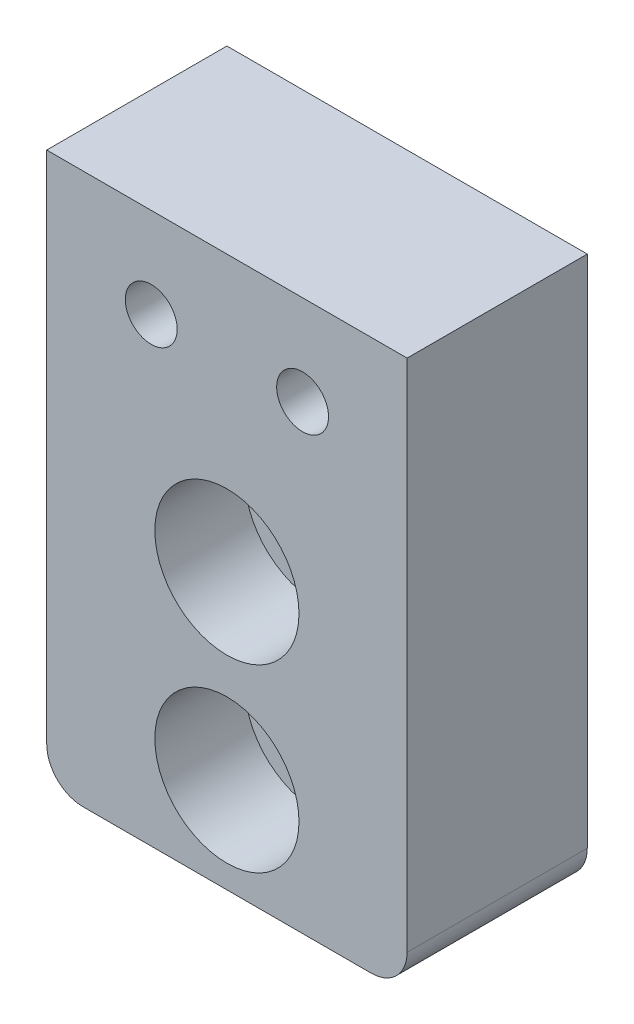
SolidWorks part; units mm, degrees
ref_plane "Front Plane" through (0, 0, 0) normal (0, 0, 1) x (1, 0, 0)
ref_plane "Top Plane" through (0, 0, 0) normal (0, 1, 0) x (1, 0, 0)
ref_plane "Right Plane" through (0, 0, 0) normal (1, 0, 0) x (0, 0, -1)
sketch "Sketch1" plane through (0, 0, 0) normal (0, 0, 1) x (1, 0, 0)
  line L1 (0, 0) -> (25.4, 0)
  line L2 (0, 0) -> (0, 38.8112)
  line L3 (0, 38.8112) -> (25.4, 38.8112)
  line L4 (25.4, 0) -> (25.4, 38.8112)
  dimension "D1" = 25.4
  dimension "D2" = 38.8112
extrude "Boss-Extrude1" add sketch "Sketch1" along normal blind 12.7
hole_wizard "CBORE for 1/4 Button Head Cap Screw1" positions "Sketch2" profile "Sketch3" counterbore size "1/4" standard "ANSI Inch" end condition through all
sketch "Sketch2" plane through (0, 0, 12.7) normal (0, 0, 1) x (1, 0, 0)
  line L0 (0, 26.1112) -> (25.4, 26.1112) construction
  line L1 (0, 38.8112) -> (0, 0) construction
  line L2 (25.4, 0) -> (25.4, 38.8112) construction
  line L3 (12.7, 38.8112) -> (12.7, 26.1112) construction
  line L4 (25.4, 38.8112) -> (0, 38.8112) construction
  line L6 (0, 26.1112) -> (25.4, 0) construction
  line L9 (12.7, 13.0556) -> (12.7, 19.4056) construction
  line L10 (12.7, 13.0556) -> (12.7, 6.7056) construction
  point P23 (12.7, 19.4056)
  point P26 (12.7, 6.7056)
  dimension "D1" = 12.7
  dimension "D2" = 6.35
  dimension "D3" = 6.35
sketch "Sketch3" plane through (12.7, 6.7056, 12.7) normal (1, 0, 0) x (0, -1, 0)
  line L0 (0, 0) -> (0, 12.7)
  line L1 (0, 12.7) -> (3.2639, 12.7)
  line L3 (3.2639, 12.7) -> (3.2639, 6.35)
  line L4 (3.2639, 6.35) -> (5.08, 6.35)
  line L5 (5.08, 6.35) -> (5.08, 0)
  line L7 (5.08, 0) -> (0, 0)
  line L11 (0, -6.35) -> (0, 107.95) construction
  dimension "Thru Hole Dia." = 6.5278
  dimension "Thru Hole Depth" = 12.7
  dimension "C'Bore Dia." = 10.16
  dimension "C'Bore Depth" = 6.35
fillet "Fillet1" radius 2.54 2 edges at (25.4, 0, 6.35) (0, 0, 6.35)
hole_wizard "CBORE for #6 Button Head Cap Screw1" positions "Sketch6" profile "Sketch5" counterbore size "#6" standard "ANSI Inch" end condition through all
sketch "Sketch6" plane through (0, 0, 0) normal (0, 0, -1) x (-1, 0, 0)
  line L0 (0, 26.1112) -> (-25.4, 26.1112) construction
  line L1 (0, 38.8112) -> (0, 2.54) construction
  line L2 (-25.4, 2.54) -> (-25.4, 38.8112) construction
  line L3 (-25.4, 38.8112) -> (0, 38.8112) construction
  line L4 (0, 26.1112) -> (-25.4, 38.8112) construction
  line L6 (-12.7, 32.4612) -> (-18.034, 32.4612) construction
  line L7 (-12.7, 32.4612) -> (-7.366, 32.4612) construction
  point P17 (-18.034, 32.4612)
  point P20 (-7.366, 32.4612)
  dimension "D1" = 12.7
  dimension "D2" = 5.334
  dimension "D3" = 5.334
sketch "Sketch5" plane through (7.366, 32.4612, 0) normal (1, 0, 0) x (0, 1, 0)
  line L0 (0, 0) -> (0, 12.7)
  line L1 (0, 12.7) -> (1.8288, 12.7)
  line L3 (1.8288, 12.7) -> (1.8288, 3.556)
  line L4 (1.8288, 3.556) -> (3.048, 3.556)
  line L5 (3.048, 3.556) -> (3.048, 0)
  line L7 (3.048, 0) -> (0, 0)
  line L11 (0, -6.35) -> (0, 107.95) construction
  dimension "Thru Hole Dia." = 3.6576
  dimension "Thru Hole Depth" = 12.7
  dimension "C'Bore Dia." = 6.096
  dimension "C'Bore Depth" = 3.556
